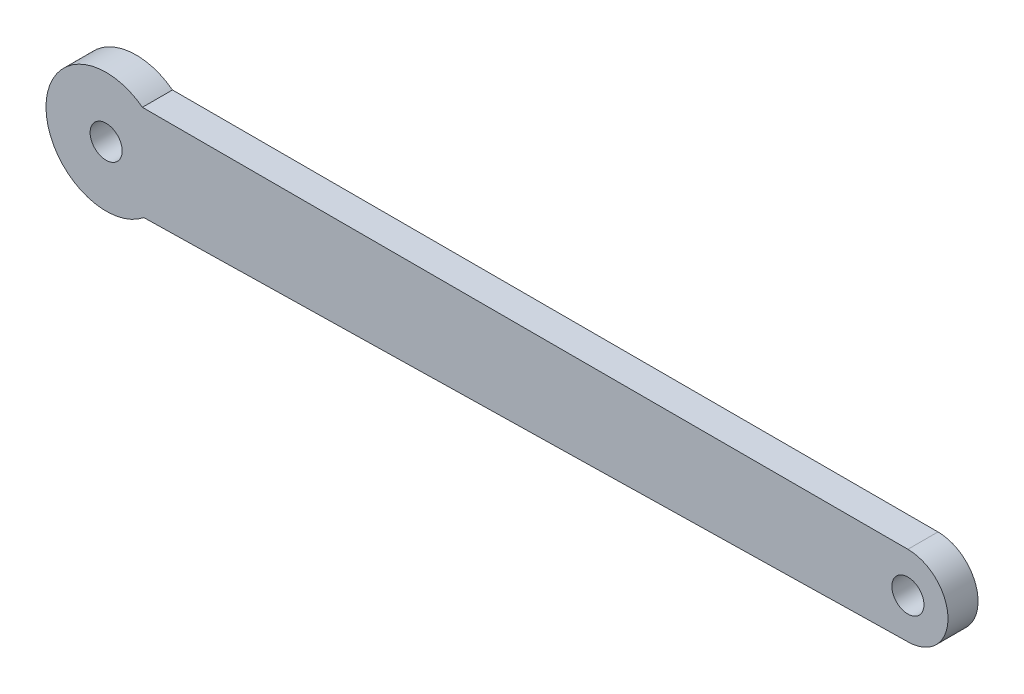
SolidWorks part; units mm, degrees
ref_plane "前视基准面" through (0, 0, 0) normal (0, 0, 1) x (1, 0, 0)
ref_plane "上视基准面" through (0, 0, 0) normal (0, 1, 0) x (1, 0, 0)
ref_plane "右视基准面" through (0, 0, 0) normal (1, 0, 0) x (0, 0, -1)
ref_plane "基准面4" through (0, 0, 3) normal (0, 0, 1) x (1, 0, 0)
sketch "草图1" plane through (0, 0, 3) normal (0, 0, 1) x (1, 0, 0)
  line L0 (23.778, 8.4676) -> (-52.5964, 8.4676)
  line L1 (-52.4516, -0.9904) -> (23.8566, 0.4686)
  arc A0 (-52.5964, 8.4676) -> (-52.4516, -0.9904) centre (-56.2156, 3.6821) ccw
  arc A1 (23.8566, 0.4686) -> (23.778, 8.4676) centre (23.778, 4.4677) ccw
extrude "凸台-拉伸1" add sketch "草图1" against normal blind 3
sketch "草图2" plane through (0, 0, 3) normal (0, 0, 1) x (1, 0, 0)
  circle A0 centre (23.778, 4.4676) radius 1.35
extrude "切除-拉伸1" cut sketch "草图2" against normal blind 2.4444
sketch "草图3" plane through (0, 0, 0) normal (0, 0, -1) x (-1, 0, 0)
  circle A0 centre (-23.778, 4.4678) radius 1.35
extrude "切除-拉伸2" cut sketch "草图3" against normal blind 0.5556
hole_wizard "Ø2.7 (2.7) 直径孔1" positions "草图5" profile "草图4" hole size "Ø2.7" standard "ANSI Metric"
sketch "草图5" plane through (0, 0, 3) normal (0, 0, 1) x (1, 0, 0)
  point P0 (-56.2156, 3.6821)
sketch "草图4" plane through (-56.2156, 3.6821, 3) normal (1, 0, 0) x (0, -1, 0)
  line L0 (0, 0) -> (0, 3)
  line L1 (0, 3) -> (1.35, 3)
  line L2 (1.35, 3) -> (1.35, 0)
  line L5 (1.35, 0) -> (0, 0)
  line L11 (0, -6.35) -> (0, 107.95) construction
  dimension "通孔孔直径" = 2.7
  dimension "通孔孔深度" = 3
sketch "草图6" plane through (0, 0, 3) normal (0, 0, 1) x (1, 0, 0)
  circle A0 centre (-56.2156, 3.6821) radius 1.6
  circle A1 centre (23.778, 4.4678) radius 1.6
  dimension "D1" = 3.2
extrude "切除-拉伸3" cut sketch "草图6" against normal through all
